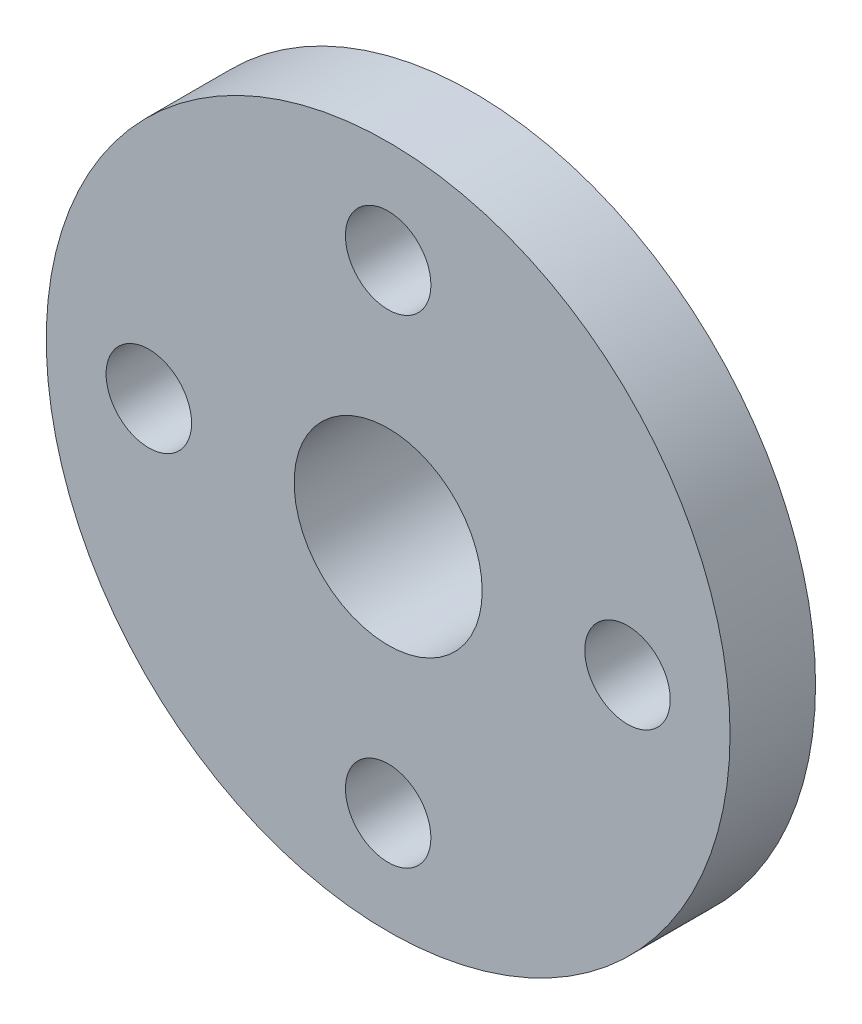
SolidWorks part; units mm, degrees
ref_plane "Front Plane" through (0, 0, 0) normal (0, 0, 1) x (1, 0, 0)
ref_plane "Top Plane" through (0, 0, 0) normal (0, 1, 0) x (1, 0, 0)
ref_plane "Right Plane" through (0, 0, 0) normal (1, 0, 0) x (0, 0, -1)
sketch "Spline_hub_envelope_Profile" plane through (0, 0, 0) normal (0, 0, 1) x (1, 0, 0)
  circle A0 centre (12.5, 0) radius 5.5
  circle A1 centre (12.5, 0) radius 2.75
extrude "Spline_hub_envelope" add sketch "Spline_hub_envelope_Profile" along normal blind 2 from offset 12.2
sketch "Disc_D20_PCD14_tap_drills_Profile" plane through (0, 0, 0) normal (0, 0, 1) x (1, 0, 0)
  circle A0 centre (12.5, 0) radius 10
  circle A1 centre (12.5, 0) radius 2.75
  circle A2 centre (19.5, 0) radius 1.25
  circle A3 centre (5.5, 0) radius 1.25
  circle A4 centre (12.5, 7) radius 1.25
  circle A5 centre (12.5, -7) radius 1.25
extrude "Disc_D20_PCD14_tap_drills" add sketch "Disc_D20_PCD14_tap_drills_Profile" along normal blind 2.5 from offset 14.2
